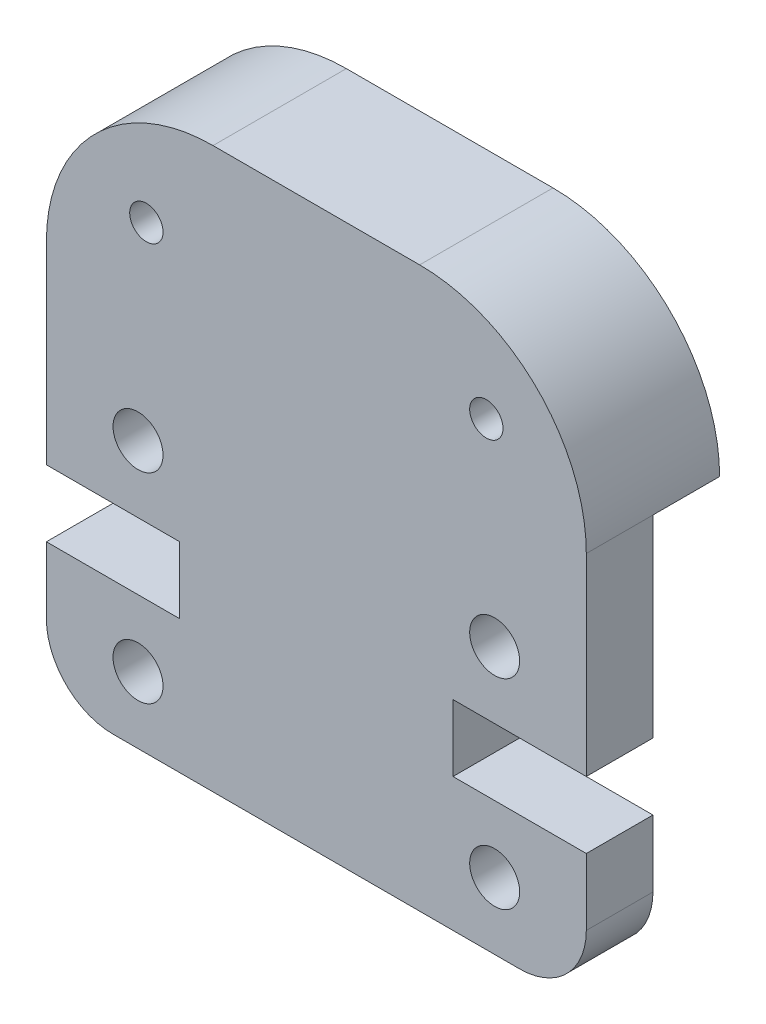
SolidWorks part; units mm, degrees
ref_plane "Front Plane" through (0, 0, 0) normal (0, 0, 1) x (1, 0, 0)
ref_plane "Top Plane" through (0, 0, 0) normal (0, 1, 0) x (1, 0, 0)
ref_plane "Right Plane" through (0, 0, 0) normal (1, 0, 0) x (0, 0, -1)
sketch "Sketch1" plane through (0, 0, 0) normal (0, 0, 1) x (1, 0, 0)
  line L0 (0, 6) -> (0, 11.795)
  line L1 (12.2, 4) -> (16.2, 4)
  line L2 (5, 16.795) -> (11.2, 16.795)
  line L3 (2, 0) -> (14.2, 0)
  line L4 (12.2, 6) -> (12.2, 4)
  line L5 (0, 2) -> (0, 4)
  line L6 (0, 6) -> (4, 6)
  line L7 (16.2, 6) -> (12.2, 6)
  line L8 (4, 6) -> (4, 4)
  line L9 (4, 4) -> (0, 4)
  line L10 (16.2, 2) -> (16.2, 4)
  line L11 (16.2, 6) -> (16.2, 11.795)
  line L12 (8.1, 16.795) -> (8.1, 0) construction
  circle A0 centre (13.45, 2) radius 0.75
  arc A1 (5, 16.795) -> (0, 11.795) centre (5, 11.795) ccw
  circle A2 centre (13.45, 8) radius 0.75
  circle A3 centre (3, 13.795) radius 0.5
  arc A4 (16.2, 2) -> (14.2, 0) centre (14.2, 2) cw
  arc A5 (0, 2) -> (2, 0) centre (2, 2) ccw
  circle A6 centre (13.2, 13.795) radius 0.5
  circle A7 centre (2.75, 8) radius 0.75
  arc A8 (11.2, 16.795) -> (16.2, 11.795) centre (11.2, 11.795) cw
  circle A9 centre (2.75, 2) radius 0.75
  dimension "D1" = 1.5
  dimension "D2" = 1
  dimension "D3" = 5
  dimension "D4" = 2
  dimension "D5" = 3
  dimension "D6" = 8.1
  dimension "D7" = 8
  dimension "D8" = 3
  dimension "D9" = 16.795
extrude "Boss-Extrude1" add sketch "Sketch1" along normal blind 4
sketch "Sketch2" plane through (0, 0, 0) normal (0, 0, 1) x (1, 0, 0)
  line L0 (0, 0) -> (0, 11.795)
  line L1 (0, 11.795) -> (16.2, 11.795)
  line L2 (16.2, 11.795) -> (16.2, 0)
  line L3 (16.2, 0) -> (0, 0)
extrude "Cut-Extrude1" cut sketch "Sketch2" along normal blind 2
equation "\"D6@Sketch1\"= \"fingerWidth@parametersSketch@prostheticParameters.SLDPRT\" / 2 'DIP width"
equation "\"D9@Sketch1\"= \"HL@parametersSketch@prostheticParameters.SLDPRT\" * 0.107 - 3 'DIP length - Sil. Sht DIP"
